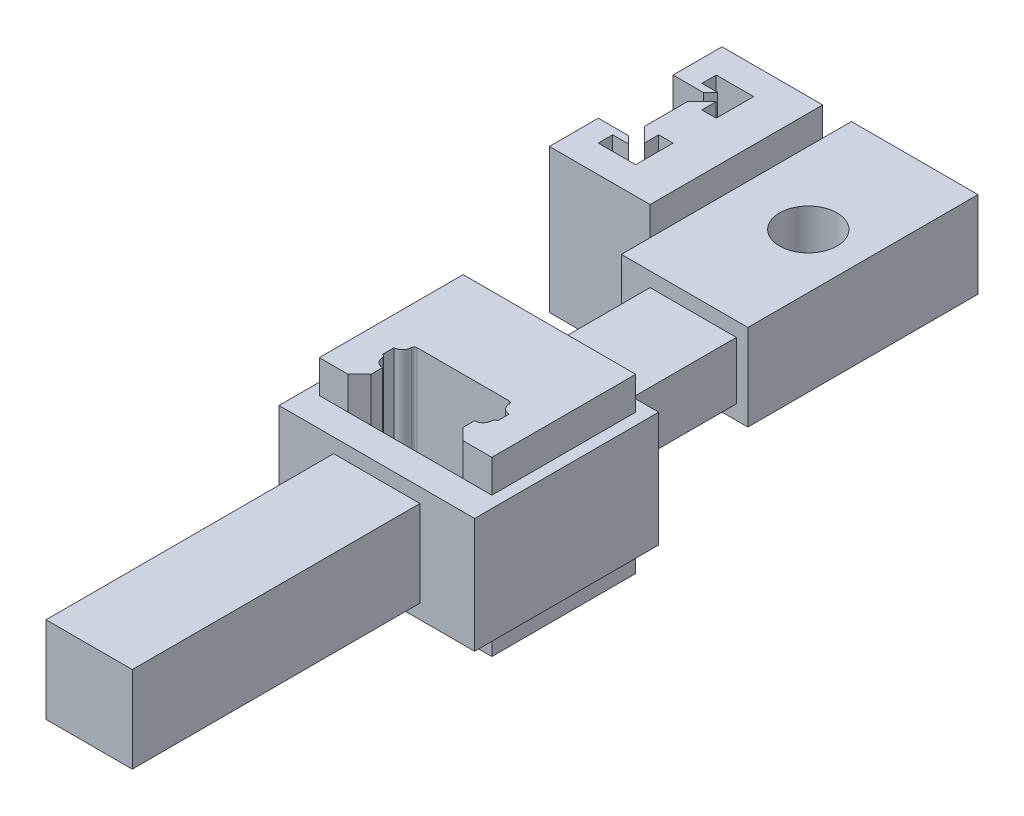
SolidWorks part; units mm, degrees
ref_plane "Front Plane" through (0, 0, 0) normal (0, 0, 1) x (1, 0, 0)
ref_plane "Top Plane" through (0, 0, 0) normal (0, 1, 0) x (1, 0, 0)
ref_plane "Right Plane" through (0, 0, 0) normal (1, 0, 0) x (0, 0, -1)
sketch "Sketch3" plane through (0, 0, 0) normal (0, 1, 0) x (1, 0, 0)
  line L1 (15, -12.5) -> (-15, -12.5)
  line L2 (15, -12.5) -> (15, 12.5)
  line L3 (15, 12.5) -> (-15, 12.5)
  line L4 (-15, -12.5) -> (-15, 12.5)
  line L5 (15, -12.5) -> (-15, 12.5) construction
  line L6 (15, 12.5) -> (-15, -12.5) construction
  point P0 (0, 0)
  dimension "D1" = 30
  dimension "D2" = 25
extrude "baseTopPlane" add sketch "Sketch3" along normal blind 30
ref_point "Point1"
sketch "Sketch6" plane through (0, 0, 12.5) normal (0, 0, 1) x (1, 0, 0)
  line L1 (-17, 4.2945) -> (17, 4.2945)
  line L2 (-17, 4.2945) -> (-17, 24.2945)
  line L3 (-17, 24.2945) -> (17, 24.2945)
  line L4 (17, 4.2945) -> (17, 24.2945)
  line L5 (-17, 4.2945) -> (17, 24.2945) construction
  line L6 (-17, 24.2945) -> (17, 4.2945) construction
  point P0 (0, 14.2945)
  point P5 (0, 0)
  dimension "D1" = 34
  dimension "D2" = 20
extrude "Boss-Extrude1" add sketch "Sketch6" against normal blind 27 and the other way blind 5
sketch "Sketch4" plane through (0, 30, 0) normal (0, 1, 0) x (1, 0, 0)
  line L0 (0, -12.5) -> (10, -12.5)
  line L1 (-15, -12.5) -> (15, -12.5) construction
  line L2 (10, -12.5) -> (8, -10.5)
  line L3 (8, -10.5) -> (8, -8.5)
  line L4 (10, -6.5) -> (10, -4.5)
  line L5 (0, -2.5) -> (0, -12.5)
  line L6 (8, -2.5) -> (0, -2.5)
  arc A0 (8, -8.5) -> (9.5, -7) centre (8, -7) ccw
  arc A1 (9.5, -7) -> (10, -6.5) centre (10, -7) cw
  arc A2 (10, -4.5) -> (8.5, -3) centre (10, -3) cw
  arc A3 (8.5, -3) -> (8, -2.5) centre (8, -3) ccw
  point P16 (0, 0)
  point P17 (0, 0)
  point P18 (0, 0)
  point P19 (9.5333, -7.5445)
  point P20 (9.5021, -7.1852)
  point P21 (9.5425, -7.615)
  point P22 (9.5874, -7.8888)
  point P23 (9.5032, -7.1685)
  point P24 (0, 0)
  point P25 (0, 0)
  point P26 (0, 0)
  point P27 (0, 0)
  point P28 (0, 0)
  point P29 (0, 0)
  point P30 (0, 0)
  point P31 (0, 0)
  point P32 (0, 0)
  point P33 (0, 0)
  point P34 (10.5227, -12.5)
  point P35 (9.4339, -12.5)
  dimension "D2" = 1.5
  dimension "D3" = 0.5
  dimension "D4" = 1.5
  dimension "D5" = 0.5
  dimension "D1" = 2
  dimension "D6" = 10
  dimension "D7" = 10
  dimension "D8" = 10
  dimension "D10" = 45
extrude "Cut-Extrude1" cut sketch "Sketch4" against normal through all
mirror "Mirror1" about plane through (0, 0, 2.5) normal (-1, 0, 0) of "Cut-Extrude1"
ref_point "outerCenterBase"
sketch "Sketch7" plane through (0, 0, -14.5) normal (0, 0, -1) x (-1, 0, 0)
  line L1 (7.5, 9.2945) -> (-7.5, 9.2945)
  line L2 (7.5, 9.2945) -> (7.5, 19.2945)
  line L3 (7.5, 19.2945) -> (-7.5, 19.2945)
  line L4 (-7.5, 9.2945) -> (-7.5, 19.2945)
  line L5 (7.5, 9.2945) -> (-7.5, 19.2945) construction
  line L6 (7.5, 19.2945) -> (-7.5, 9.2945) construction
  point P1 (0, 14.2945)
  dimension "D1" = 15
  dimension "D2" = 10
extrude "BackBar" add sketch "Sketch7" along normal blind 60
sketch "Sketch8" plane through (-7.5, 0, 0) normal (-1, 0, 0) x (0, 0, 1)
  line L1 (-37.5, 6.7945) -> (-77.5, 6.7945)
  line L2 (-37.5, 6.7945) -> (-37.5, 21.7945)
  line L3 (-37.5, 21.7945) -> (-77.5, 21.7945)
  line L4 (-77.5, 6.7945) -> (-77.5, 21.7945)
  line L5 (-37.5, 6.7945) -> (-77.5, 21.7945) construction
  line L6 (-37.5, 21.7945) -> (-77.5, 6.7945) construction
  line L9 (-74.5, 19.2945) -> (-14.5, 19.2945) construction
  line L12 (12.5, 0) -> (12.5, 4.2945) construction
  point P0 (-57.5, 14.2945)
  dimension "D1" = 70
  dimension "D2" = 15
  dimension "D3" = 40
  dimension "D4" = 5
extrude "sideConnect" add sketch "Sketch8" against normal blind 17 and the other way blind 5
ref_point "sideRef"
sketch "Sketch9" plane through (-12.5, 0, 0) normal (-1, 0, 0) x (0, 0, 1)
  line L1 (-42.5, 1.7945) -> (-72.5, 1.7945)
  line L2 (-42.5, 1.7945) -> (-42.5, 26.7945)
  line L3 (-42.5, 26.7945) -> (-72.5, 26.7945)
  line L4 (-72.5, 1.7945) -> (-72.5, 26.7945)
  line L5 (-42.5, 1.7945) -> (-72.5, 26.7945) construction
  line L6 (-42.5, 26.7945) -> (-72.5, 1.7945) construction
  point P0 (-57.5, 14.2945)
  dimension "D1" = 30
  dimension "D2" = 25
extrude "sideSlider" add sketch "Sketch9" along normal blind 17.5
sketch "Sketch13" plane through (0, 26.7945, 0) normal (0, 1, 0) x (1, 0, 0)
  line L0 (-30, 64) -> (-30, 51)
  line L3 (-30, 42.5) -> (-30, 72.5) construction
  line L4 (-30, 51) -> (-24.75, 51)
  line L5 (-24.75, 51) -> (-23.5, 49.75)
  line L6 (-23.5, 49.75) -> (-26.25, 49.75)
  line L7 (-26.25, 49.75) -> (-26.25, 47.25)
  line L8 (-26.25, 47.25) -> (-19.75, 47.25)
  line L9 (-19.75, 47.25) -> (-19.75, 53.75)
  line L10 (-19.75, 53.75) -> (-22.25, 53.75)
  line L11 (-22.25, 53.75) -> (-22.25, 51.25)
  line L12 (-22.25, 51.25) -> (-24.75, 53.75)
  line L13 (-24.75, 53.75) -> (-24.75, 61.25)
  line L14 (-24.75, 61.25) -> (-22.25, 63.75)
  line L15 (-22.25, 63.75) -> (-22.25, 61.25)
  line L16 (-22.25, 61.25) -> (-19.75, 61.25)
  line L17 (-19.75, 61.25) -> (-19.75, 67.75)
  line L18 (-19.75, 67.75) -> (-26.25, 67.75)
  line L19 (-26.25, 67.75) -> (-26.25, 65.25)
  line L20 (-26.25, 65.25) -> (-23.5, 65.25)
  line L21 (-23.5, 65.25) -> (-24.75, 64)
  line L22 (-24.75, 64) -> (-30, 64)
  point P16 (-30, 57.5)
  point P23 (0, 0)
  point P24 (-21, 61.25)
  point P25 (-24.75, 57.5)
  dimension "D1" = 13
  dimension "D2" = 2.5
  dimension "D3" = 2.5
  dimension "D4" = 2.5
  dimension "D5" = 2.5
  dimension "D6" = 7.5
  dimension "D7" = 5.25
  dimension "D8" = 9
  dimension "D9" = 1.25
  dimension "D10" = 1.25
  dimension "D11" = 2.5
  dimension "D12" = 2.5
  dimension "D13" = 6.5
  dimension "D14" = 6.5
  dimension "D15" = 6.5
extrude "mountingCut" cut sketch "Sketch13" against normal through all
hole_wizard "DrillforMovement" positions "Sketch14" profile "Sketch15" hole size "Ø10.0" standard "ANSI Metric" end condition up to next
sketch "Sketch14" plane through (0, 21.7945, 0) normal (0, 1, 0) x (1, 0, 0)
  line L0 (9.5, 37.5) -> (9.5, 77.5) construction
  point P0 (0, 57.5)
  point P4 (0, 0)
  point P7 (9.5, 57.5)
sketch "Sketch15" plane through (0, 21.7945, -57.5) normal (1, 0, 0) x (0, 0, 1)
  line L0 (0, 0) -> (0, 15)
  line L1 (0, 15) -> (5, 15)
  line L2 (5, 15) -> (5, 0)
  line L5 (5, 0) -> (0, 0)
  line L11 (0, -6.35) -> (0, 107.95) construction
  dimension "Thru Hole Dia." = 10
  dimension "Thru Hole Depth" = 15
ref_point "frontBarRef"
sketch "Sketch17" plane through (0, 0, 17.5) normal (0, 0, 1) x (1, 0, 0)
  line L1 (7.5, 6.7945) -> (-7.5, 6.7945)
  line L2 (7.5, 6.7945) -> (7.5, 21.7945)
  line L3 (7.5, 21.7945) -> (-7.5, 21.7945)
  line L4 (-7.5, 6.7945) -> (-7.5, 21.7945)
  line L5 (7.5, 6.7945) -> (-7.5, 21.7945) construction
  line L6 (7.5, 21.7945) -> (-7.5, 6.7945) construction
  point P0 (0, 14.2945)
  dimension "D1" = 15
  dimension "D2" = 15
extrude "frontBar" add sketch "Sketch17" along normal blind 50
